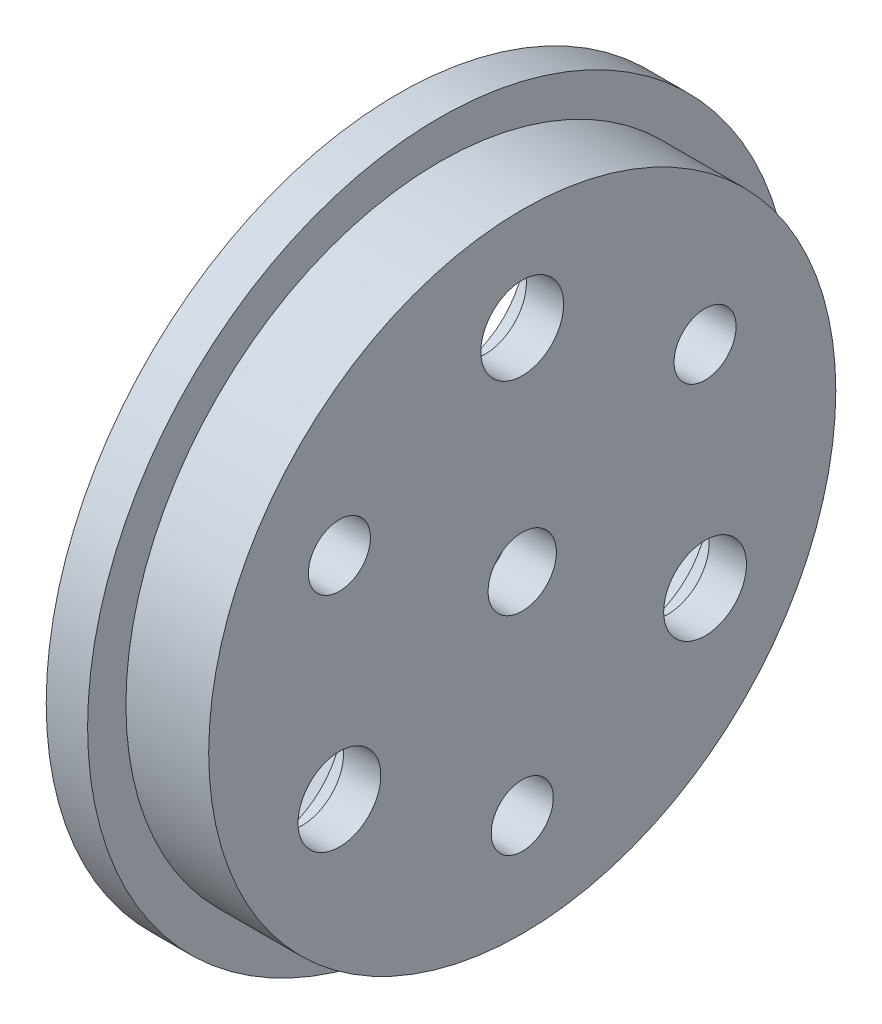
SolidWorks part; units mm, degrees
ref_plane "前视基准面" through (0, 0, 0) normal (0, 0, 1) x (1, 0, 0)
ref_plane "上视基准面" through (0, 0, 0) normal (0, 1, 0) x (1, 0, 0)
ref_plane "右视基准面" through (0, 0, 0) normal (1, 0, 0) x (0, 0, -1)
other "Configuration Table"
sketch "草图4" plane through (0, 0, 0) normal (1, 0, 0) x (0, 0, -1)
  circle A0 centre (0, 0) radius 17
extrude "凸台-拉伸2" add sketch "草图4" along normal blind 2
sketch "草图5" plane through (2, 0, 0) normal (1, 0, 0) x (0, 0, -1)
  circle A0 centre (0, 0) radius 15.15
  dimension "D1" = 30.3
extrude "凸台-拉伸3" add sketch "草图5" along normal blind 4
sketch "草图6" plane through (0, 0, 0) normal (-1, 0, 0) x (0, 0, 1)
  line L0 (0, 0) -> (0, 18) construction
  line L1 (0, 0) -> (15.5885, -9) construction
  line L2 (0, 0) -> (-15.5885, -9) construction
  line L3 (-3.0311, 12.75) -> (-12.5574, -3.75)
  line L4 (-9.5263, -9) -> (9.5263, -9)
  line L5 (12.5574, -3.75) -> (3.0311, 12.75)
  arc A0 (9.5263, -9) -> (12.5574, -3.75) centre (9.5263, -5.5) ccw
  arc A1 (-12.5574, -3.75) -> (-9.5263, -9) centre (-9.5263, -5.5) ccw
  arc A2 (-3.0311, 12.75) -> (3.0311, 12.75) centre (0, 11) cw
  point P7 (0, 0)
  dimension "D3" = 3.5
  dimension "D1" = 18
  dimension "D2" = 3
extrude "切除-拉伸1" cut sketch "草图6" against normal blind 2.6
sketch "草图7" plane through (2.6, 0, 0) normal (-1, 0, 0) x (0, 0, 1)
  line L0 (0, 0) -> (0, 10.2)
  line L1 (0, 0) -> (8.8335, -5.1)
  line L2 (0, 0) -> (-8.8335, -5.1)
  circle A0 centre (0, 10.2) radius 3.55
  circle A1 centre (8.8335, -5.1) radius 3.55
  circle A2 centre (-8.8335, -5.1) radius 3.55
  point P10 (0, 0)
  dimension "D1" = 7.1
  dimension "D2" = 3
extrude "切除-拉伸2" cut sketch "草图7" against normal blind 1.6
sketch "草图8" plane through (2.6, 0, 0) normal (-1, 0, 0) x (0, 0, 1)
  line L0 (0, 0) -> (0, 10.2)
  line L1 (0, 0) -> (8.8335, -5.1)
  line L2 (0, 0) -> (-8.8335, -5.1)
  circle A0 centre (0, 10.2) radius 2
  circle A1 centre (8.8335, -5.1) radius 2
  circle A2 centre (-8.8335, -5.1) radius 2
  point P11 (0, 0)
  dimension "D1" = 4
  dimension "D2" = 3
extrude "切除-拉伸3" cut sketch "草图8" against normal through all
sketch "草图9" plane through (2.6, 0, 0) normal (-1, 0, 0) x (0, 0, 1)
  circle A0 centre (0, 0) radius 5.5
  dimension "D1" = 11
extrude "切除-拉伸4" cut sketch "草图9" against normal blind 1.1
sketch "草图11" plane through (3.7, 0, 0) normal (-1, 0, 0) x (0, 0, 1)
  circle A0 centre (0, 0) radius 1.65
  dimension "D1" = 3.3
extrude "切除-拉伸5" cut sketch "草图11" against normal through all
sketch "草图13" plane through (6, 0, 0) normal (1, 0, 0) x (0, 0, -1)
  line L0 (0, 0) -> (0, 10.2)
  line L1 (0, 0) -> (-8.8335, 5.1)
  circle A1 centre (-8.8335, 5.1) radius 1.5
  circle A2 centre (8.8335, 5.1) radius 1.5
  circle A3 centre (0, -10.2) radius 1.5
  point P12 (0, 0)
  dimension "D3" = 3
  dimension "D1" = 10.2
  dimension "D2" = 60
extrude "切除-拉伸6" cut sketch "草图13" against normal through all
